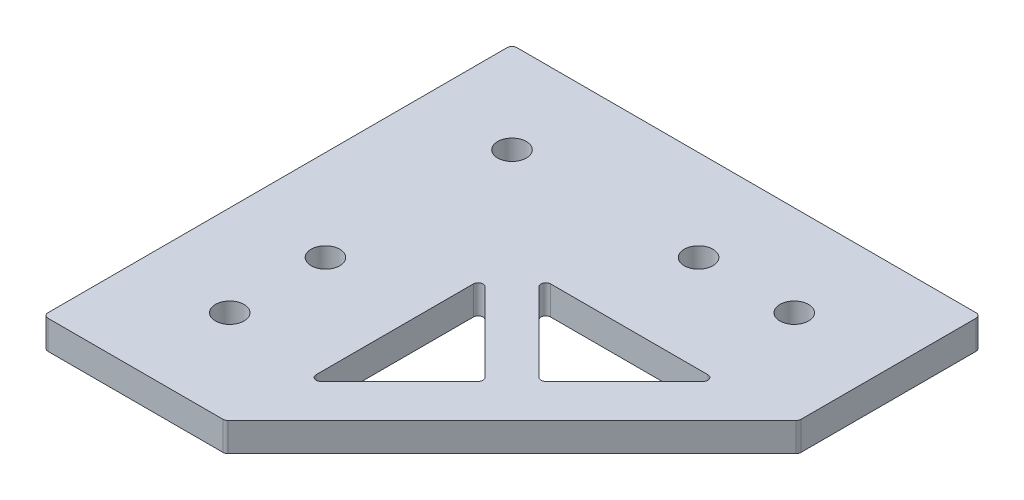
SolidWorks part; units mm, degrees
material "Thornel Mat VMA"
ref_plane "Front Plane" through (0, 0, 0) normal (0, 0, 1) x (1, 0, 0)
ref_plane "Top Plane" through (0, 0, 0) normal (0, 1, 0) x (1, 0, 0)
ref_plane "Right Plane" through (0, 0, 0) normal (1, 0, 0) x (0, 0, -1)
sketch "Sketch1" plane through (0, 0, 0) normal (0, 1, 0) x (1, 0, 0)
  line L0 (0, -9.5) -> (49, -9.5) construction
  line L1 (0, 0) -> (49, 0)
  line L2 (0, 0) -> (0, -19)
  line L4 (49, 0) -> (49, -19)
  line L6 (0, -19) -> (0, -49)
  line L7 (0, -49) -> (19, -49)
  line L9 (9.5, -49) -> (9.5, 0) construction
  line L11 (49, -19) -> (19, -49)
  circle A0 centre (9.5, -9.5) radius 1.5
  circle A1 centre (39, -9.5) radius 1.5
  circle A2 centre (9.5, -39) radius 1.5
  circle A3 centre (9.5, -29) radius 1.5
  circle A4 centre (29, -9.5) radius 1.5
  dimension "D5" = 3
  dimension "D10" = 10
  dimension "D11" = 10
  dimension "D13" = 10
  dimension "D1" = 19
  dimension "D2" = 19
  dimension "D3" = 49
  dimension "D4" = 49
  dimension "D12" = 10
extrude "Boss-Extrude1" add sketch "Sketch1" along normal blind 3
fillet "Fillet1" radius 0.5 5 edges at (0, 1.5, 0) (49, 1.5, 0) (0, 1.5, 49) (49, 1.5, 19) (19, 1.5, 49)
sketch "Sketch2" plane through (0, 3, 0) normal (0, 1, 0) x (1, 0, 0)
  line L0 (18.7929, -49) -> (18.7929, 0) construction
  line L1 (48.5, 0) -> (0.5, 0) construction
  line L2 (49, -18.7929) -> (0, -18.7929) construction
  line L3 (0, -0.5) -> (0, -48.5) construction
  line L4 (23.6584, -19.6229) -> (40.0989, -19.6229)
  line L5 (40.4525, -20.4764) -> (32.2322, -28.6967)
  line L6 (31.5251, -28.6967) -> (23.3049, -20.4764)
  line L7 (20.4764, -23.3049) -> (28.6967, -31.5251)
  line L8 (28.6967, -32.2322) -> (20.4764, -40.4525)
  line L9 (19.6229, -40.0989) -> (19.6229, -23.6584)
  line L10 (19.1464, -48.8536) -> (48.8536, -19.1464) construction
  arc A0 (40.0989, -19.6229) -> (40.4525, -20.4764) centre (40.0989, -20.1229) cw
  arc A1 (23.6584, -19.6229) -> (23.3049, -20.4764) centre (23.6584, -20.1229) ccw
  arc A2 (32.2322, -28.6967) -> (31.5251, -28.6967) centre (31.8787, -28.3431) cw
  arc A3 (28.6967, -31.5251) -> (28.6967, -32.2322) centre (28.3431, -31.8787) cw
  arc A4 (20.4764, -40.4525) -> (19.6229, -40.0989) centre (20.1229, -40.0989) cw
  arc A5 (20.4764, -23.3049) -> (19.6229, -23.6584) centre (20.1229, -23.6584) ccw
  dimension "D7" = 0.5
  dimension "D1" = 4
  dimension "D2" = 18.7929
  dimension "D3" = 5
  dimension "D4" = 5
  dimension "D5" = 0.83
  dimension "D6" = 0.83
extrude "Cut-Extrude1" cut sketch "Sketch2" against normal blind 3
